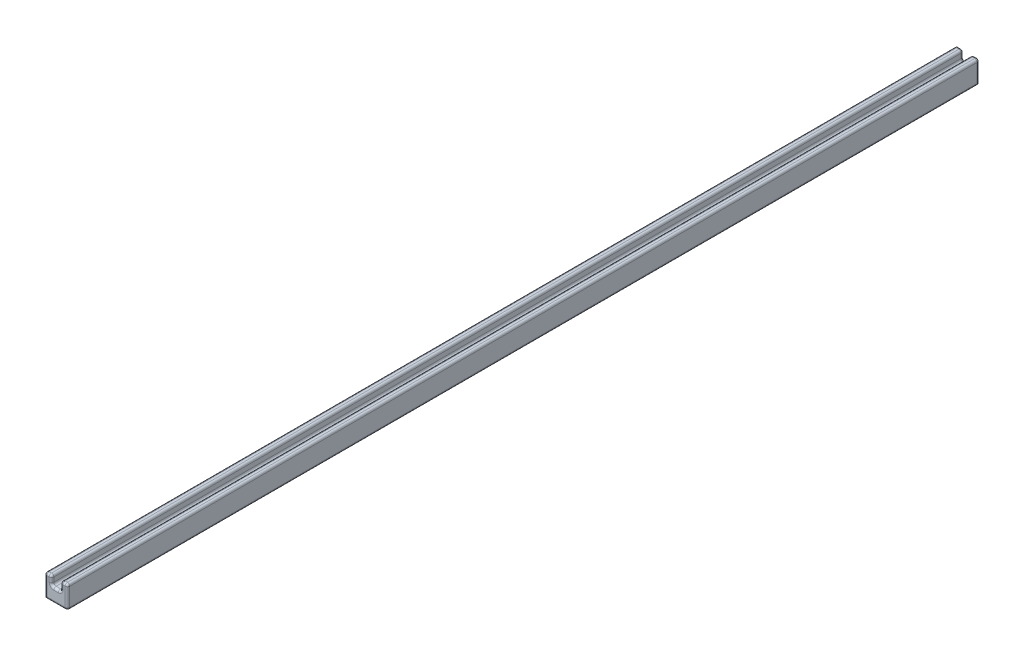
SolidWorks part; units mm, degrees
ref_plane "Front Plane" through (0, 0, 0) normal (0, 0, 1) x (1, 0, 0)
ref_plane "Top Plane" through (0, 0, 0) normal (0, 1, 0) x (1, 0, 0)
ref_plane "Right Plane" through (0, 0, 0) normal (1, 0, 0) x (0, 0, -1)
sketch "Sketch1" plane through (0, 0, 0) normal (0, 0, 1) x (1, 0, 0)
  line L1 (10.7857, -3.0265) -> (15.7857, -3.0265)
  line L2 (10.7857, -3.0265) -> (10.7857, -8.0265)
  line L3 (10.7857, -8.0265) -> (15.7857, -8.0265)
  line L4 (15.7857, -3.0265) -> (15.7857, -8.0265)
  line L5 (12.2857, -3.0265) -> (14.2857, -3.0265)
  line L6 (12.2857, -3.0265) -> (12.2857, -5.0265)
  line L7 (12.2857, -5.0265) -> (14.2857, -5.0265)
  line L8 (14.2857, -3.0265) -> (14.2857, -5.0265)
  dimension "D1" = 5
  dimension "D2" = 5
  dimension "D3" = 2
  dimension "D4" = 2
  dimension "D5" = 1.5
extrude "Boss-Extrude1" add sketch "Sketch1" against normal blind 200 contours L1 L8 L7 L6 L2 L3 L4
fillet "Fillet1" radius 0.5 21 edges at (14.2857, -4.0265, -200) (15.0357, -3.0265, 0) (14.2857, -4.0265, 0) (13.2857, -5.0265, 0) (12.2857, -4.0265, 0) (11.5357, -3.0265, 0) (10.7857, -5.5265, 0) (13.2857, -8.0265, 0) (15.7857, -5.5265, 0) (15.0357, -3.0265, -200) (13.2857, -5.0265, -200) (12.2857, -4.0265, -200) (11.5357, -3.0265, -200) (15.7857, -5.5265, -200) (14.2857, -3.0265, -100) (14.2857, -5.0265, -100) (12.2857, -5.0265, -100) (12.2857, -3.0265, -100) (10.7857, -3.0265, -100) (15.7857, -8.0265, -100) (15.7857, -3.0265, -100)
equation "\"BeamLength\" = 200"
equation "\"BeamWidth\" = 5"
equation "\"BeamHeight\" = 5"
equation "\"ChannelWidth\" = 2"
equation "\"ChannelDepth\"= 2"
equation "\"D1@Sketch1\"=\"BeamWidth\""
equation "\"D2@Sketch1\"=\"BeamHeight\""
equation "\"D3@Sketch1\"=\"ChannelDepth\""
equation "\"D4@Sketch1\"=\"ChannelWidth\""
equation "\"D5@Sketch1\"=(\"BeamWidth\"-\"ChannelWidth\")/2"
equation "\"D1@Boss-Extrude1\"=\"BeamLength\""
